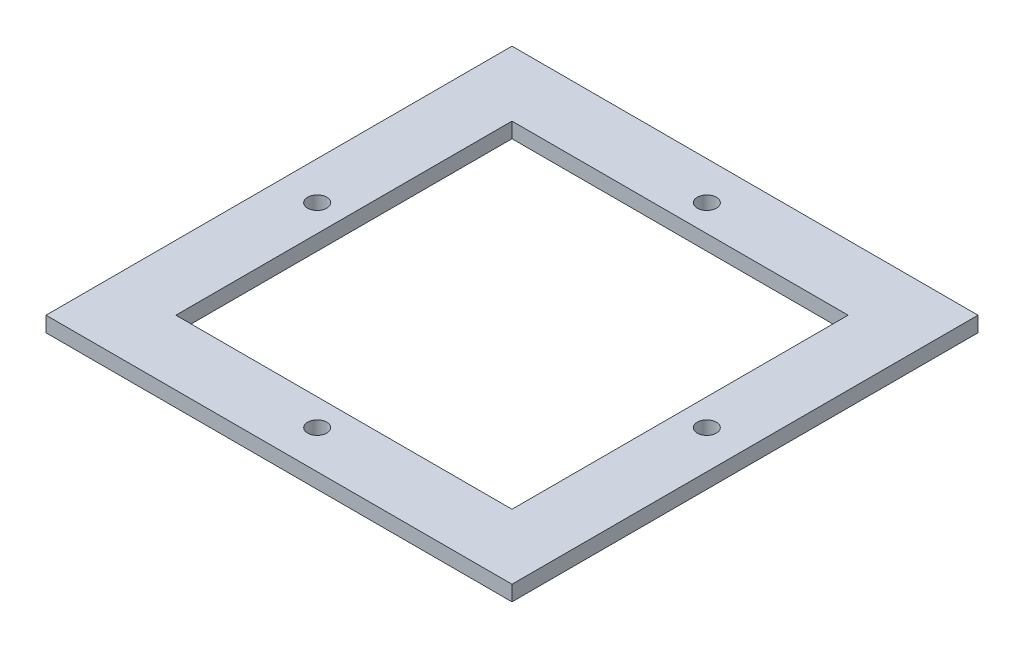
SolidWorks part; units mm, degrees
ref_plane "Front Plane" through (0, 0, 0) normal (0, 0, 1) x (1, 0, 0)
ref_plane "Top Plane" through (0, 0, 0) normal (0, 1, 0) x (1, 0, 0)
ref_plane "Right Plane" through (0, 0, 0) normal (1, 0, 0) x (0, 0, -1)
sketch "Sketch1" plane through (0, 0, 0) normal (0, 1, 0) x (1, 0, 0)
  line L0 (-61, 0) -> (61, 0)
  line L1 (61, -61) -> (-61, -61)
  line L2 (61, -61) -> (61, 61)
  line L3 (61, 61) -> (-61, 61)
  line L4 (-61, -61) -> (-61, 61)
  line L5 (61, -61) -> (-61, 61) construction
  line L6 (61, 61) -> (-61, -61) construction
  line L7 (44, -44) -> (-44, -44)
  line L8 (44, -44) -> (44, 44)
  line L9 (44, 44) -> (-44, 44)
  line L10 (-44, -44) -> (-44, 44)
  line L11 (44, -44) -> (-44, 44) construction
  line L12 (44, 44) -> (-44, -44) construction
  line L13 (0, 61) -> (0, -61)
  circle A0 centre (-51, 0) radius 2.5
  circle A1 centre (51, 0) radius 2.5
  circle A2 centre (0, 51) radius 2.5
  circle A3 centre (0, -51) radius 2.5
  point P0 (0, 0)
  point P6 (0, 0)
  point P11 (-61, 0)
  point P12 (61, 0)
  point P13 (0, 61)
  point P14 (0, -61)
  point P17 (-51, 0)
  point P22 (-44, 0)
  point P23 (-44, 0)
  point P24 (-51, 0)
  point P26 (-51, 0)
  point P28 (0, 51)
  dimension "D6" = 5
  dimension "D8" = 5
  dimension "D1" = 122
  dimension "D2" = 122
  dimension "D3" = 88
  dimension "D4" = 88
  dimension "D5" = 51
  dimension "D7" = 51
extrude "Boss-Extrude1" add sketch "Sketch1" along normal blind 4 contours L13 A3 L7 L10 L0 A0 L4 L1 | L13 A3 L1 L2 L0 A1 L8 L7 | A2 L13 L9 L8 L0 A1 L2 L3 | A2 L13 L3 L4 L0 A0 L10 L9
